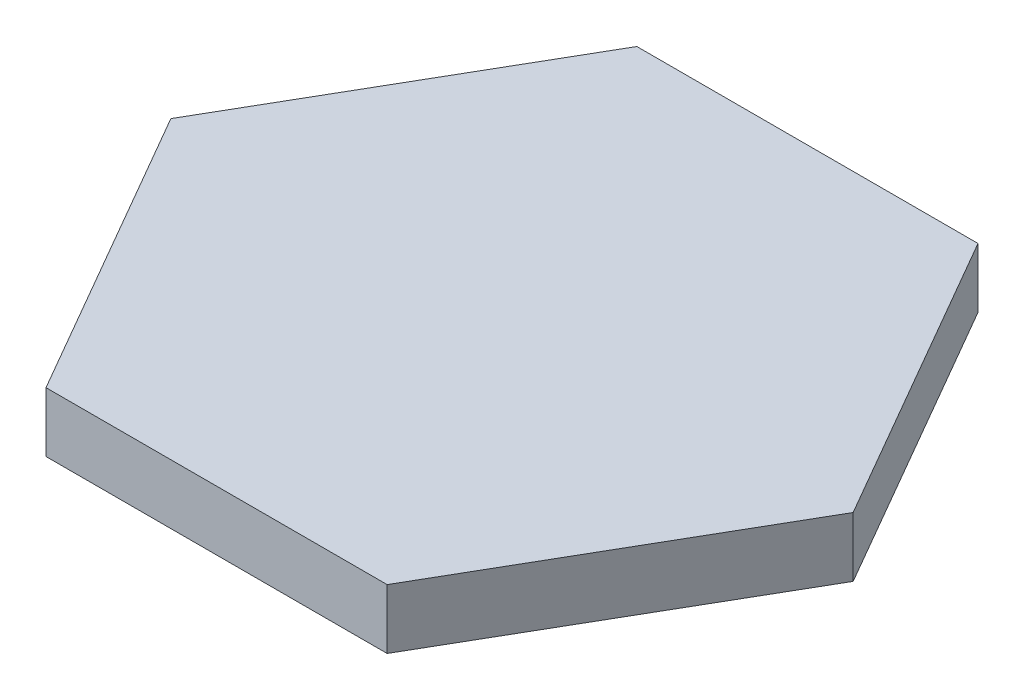
SolidWorks part; units mm, degrees
material "Teak"
ref_plane "Front Plane" through (0, 0, 0) normal (0, 0, 1) x (1, 0, 0)
ref_plane "Top Plane" through (0, 0, 0) normal (0, 1, 0) x (1, 0, 0)
ref_plane "Right Plane" through (0, 0, 0) normal (1, 0, 0) x (0, 0, -1)
sketch "Sketch1" plane through (0, 0, 0) normal (0, 1, 0) x (1, 0, 0)
  line L1 (45.74, 0) -> (22.87, 39.612)
  line L2 (22.87, 39.612) -> (-22.87, 39.612)
  line L3 (-22.87, 39.612) -> (-45.74, 0)
  line L4 (-45.74, 0) -> (-22.87, -39.612)
  line L5 (-22.87, -39.612) -> (22.87, -39.612)
  line L6 (22.87, -39.612) -> (45.74, 0)
  circle A0 centre (0, 0) radius 39.612 construction
  dimension "D1" = 79.224
extrude "Boss-Extrude1" add sketch "Sketch1" along normal blind 8
